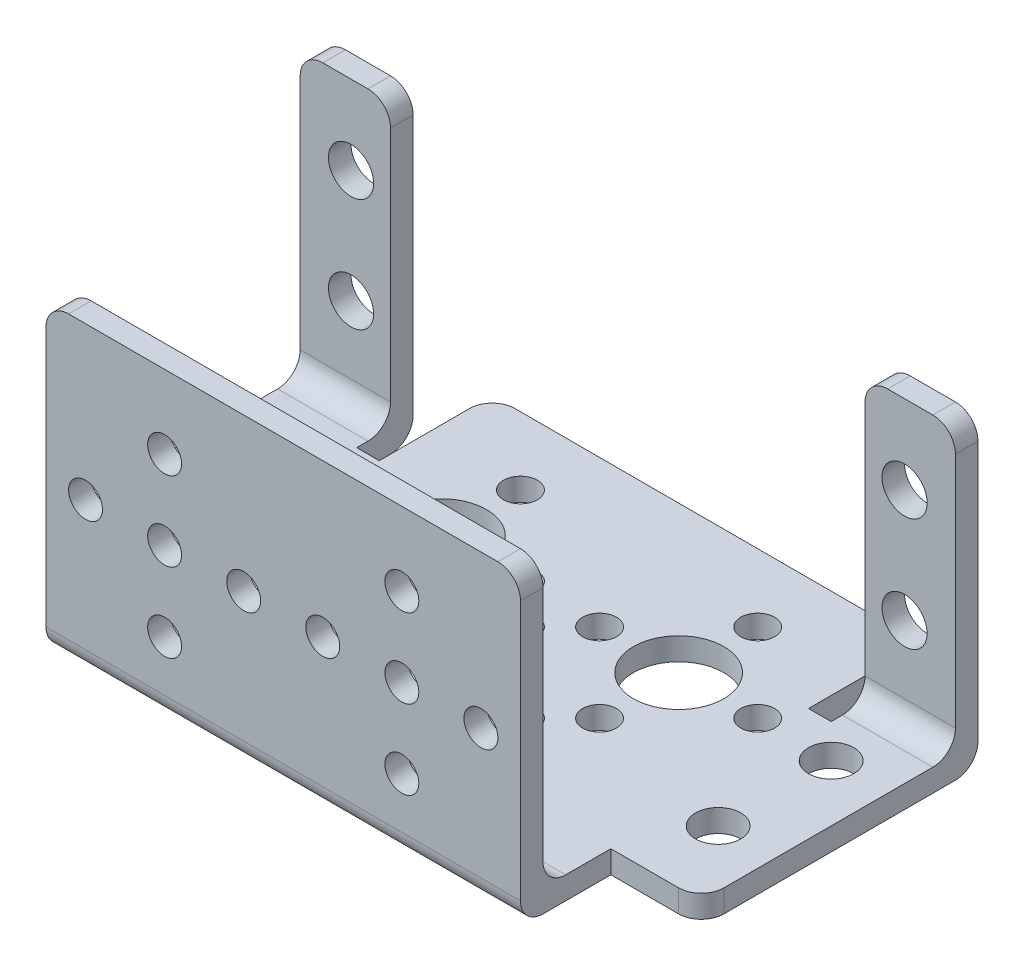
SolidWorks part; units mm, degrees
ref_plane "前视基准面" through (0, 0, 0) normal (0, 0, 1) x (1, 0, 0)
ref_plane "上视基准面" through (0, 0, 0) normal (0, 1, 0) x (1, 0, 0)
ref_plane "右视基准面" through (0, 0, 0) normal (1, 0, 0) x (0, 0, -1)
sketch "草图1" plane through (0, 0, 0) normal (0, 1, 0) x (1, 0, 0)
  line L0 (-46.5016, 0) -> (46.5016, 0) construction
  line L5 (0, 0) -> (0, -24.5) construction
  line L6 (0, -24.5) -> (21, -24.5)
  line L7 (21, -24.5) -> (21, -16.5)
  line L8 (21, -16.5) -> (27, -16.5)
  line L9 (29, -14.5) -> (29, 8)
  line L10 (29, 8) -> (21, 8)
  line L11 (21, 8) -> (21, 3)
  line L12 (21, 3) -> (19, 3)
  line L13 (19, 3) -> (19, 11)
  line L14 (17, 13) -> (0, 13)
  line L15 (0, 13) -> (0, -24.5)
  line L17 (24, 0) -> (24, -10) construction
  circle A0 centre (0, -10.5) radius 7 construction
  circle A1 centre (0, -10.5) radius 4
  circle A2 centre (10.5, 0) radius 4
  circle A3 centre (10.5, 0) radius 7 construction
  circle A4 centre (17.5, 0) radius 1.5
  circle A5 centre (10.5, 7) radius 1.5
  circle A6 centre (10.5, -7) radius 1.5
  circle A7 centre (3.5, 0) radius 1.5
  circle A8 centre (0, -3.5) radius 1.5
  circle A9 centre (7, -10.5) radius 1.5
  circle A10 centre (0, -17.5) radius 1.5
  circle A11 centre (24, 0) radius 2
  circle A12 centre (24, -10) radius 2
  arc A13 (27, -16.5) -> (29, -14.5) centre (27, -14.5) ccw
  arc A14 (19, 11) -> (17, 13) centre (17, 11) ccw
  dimension "D1" = 4
  dimension "D4" = 8
  dimension "D5" = 14
  dimension "D12" = 2
  dimension "D13" = 3
  dimension "D14" = 8
  dimension "D2" = 10
  dimension "D3" = 14
  dimension "D6" = 10.5
  dimension "D7" = 19
  dimension "D8" = 29
  dimension "D9" = 37.5
  dimension "D10" = 32.5
  dimension "D11" = 14.5
  dimension "D15" = 21
  dimension "D16" = 24
  dimension "D17" = 5
  dimension "D18" = 8
extrude "凸台-拉伸1" add sketch "草图1" along normal blind 2 contours L13 A14 L14 L15 A8 A1 A10 L6 L7 L8 A13 L9 L10 L11 L12 A2 A4 A5 A6 A7 A9 A11 A12
sketch "草图2" plane through (0, 2, 0) normal (0, 1, 0) x (1, 0, 0)
  line L0 (29, -14.5) -> (29, 8) construction
  line L1 (21, 8) -> (29, 8)
  line L2 (21, 8) -> (21, 6)
  line L3 (21, 6) -> (29, 6)
  line L4 (29, 8) -> (29, 6)
  dimension "D1" = 2
extrude "凸台-拉伸2" add sketch "草图2" along normal blind 25
sketch "草图3" plane through (0, 0, -6) normal (0, 0, 1) x (1, 0, 0)
  line L0 (24.5, 20) -> (24.5, 10) construction
  line L1 (21, 27) -> (29, 27) construction
  line L6 (21, 23.4829) -> (21, 25)
  line L7 (21, 27) -> (21, 2) construction
  line L8 (23, 27) -> (27, 27)
  line L9 (29, 25) -> (29, 22.6837)
  line L10 (29, 27) -> (29, 2) construction
  circle A0 centre (24.5, 20) radius 2
  circle A1 centre (24.5, 10) radius 2
  arc A3 (27, 27) -> (29, 25) centre (27, 25) cw
  arc A4 (21, 25) -> (23, 27) centre (23, 25) cw
  point P22 (29, 27)
  point P25 (21, 27)
  dimension "D1" = 4
  dimension "D4" = 2
  dimension "D2" = 10
  dimension "D3" = 7
  dimension "D5" = 3.5
extrude "切除-拉伸1" cut sketch "草图3" against normal through all
mirror "镜向1" about plane through (0, 2, 0) normal (1, 0, 0) of "切除-拉伸1", "凸台-拉伸2", "凸台-拉伸1"
sketch "草图4" plane through (0, 2, 0) normal (0, 1, 0) x (1, 0, 0)
  line L0 (21, -24.5) -> (21, -16.5) construction
  line L1 (-21, -24.5) -> (21, -24.5)
  line L2 (-21, -24.5) -> (-21, -22.5)
  line L3 (-21, -22.5) -> (21, -22.5)
  line L4 (21, -24.5) -> (21, -22.5)
  dimension "D1" = 2
extrude "凸台-拉伸3" add sketch "草图4" along normal blind 25
sketch "草图5" plane through (0, 0, 24.5) normal (0, 0, 1) x (1, 0, 0)
  line L0 (-21, 13.5) -> (21, 13.5) construction
  line L1 (-21, 25) -> (-21, 2) construction
  line L2 (21, 27) -> (21, 0) construction
  circle A0 centre (-10.5, 13.5) radius 1.5
  circle A1 centre (10.5, 13.5) radius 1.5
  circle A2 centre (10.5, 13.5) radius 7 construction
  circle A3 centre (-10.5, 13.5) radius 7 construction
  circle A4 centre (-10.5, 20.5) radius 1.5
  circle A5 centre (-3.5, 13.5) radius 1.5
  circle A6 centre (-10.5, 6.5) radius 1.5
  circle A7 centre (-17.5, 13.5) radius 1.5
  circle A8 centre (10.5, 20.5) radius 1.5
  circle A9 centre (17.5, 13.5) radius 1.5
  circle A10 centre (10.5, 6.5) radius 1.5
  circle A11 centre (3.5, 13.5) radius 1.5
  dimension "D1" = 3
  dimension "D2" = 14
  dimension "D3" = 3
  dimension "D4" = 10.5
  dimension "D5" = 10.5
extrude "切除-拉伸2" cut sketch "草图5" against normal blind 25
fillet "圆角1" radius 2 2 edges at (21, 27, 23.5) (-21, 27, 23.5)
fillet "圆角2" radius 2 6 edges at (0, 2, 22.5) (0, 0, 24.5) (-25, 2, -6) (-25, 0, -8) (25, 2, -6) (25, 0, -8)
